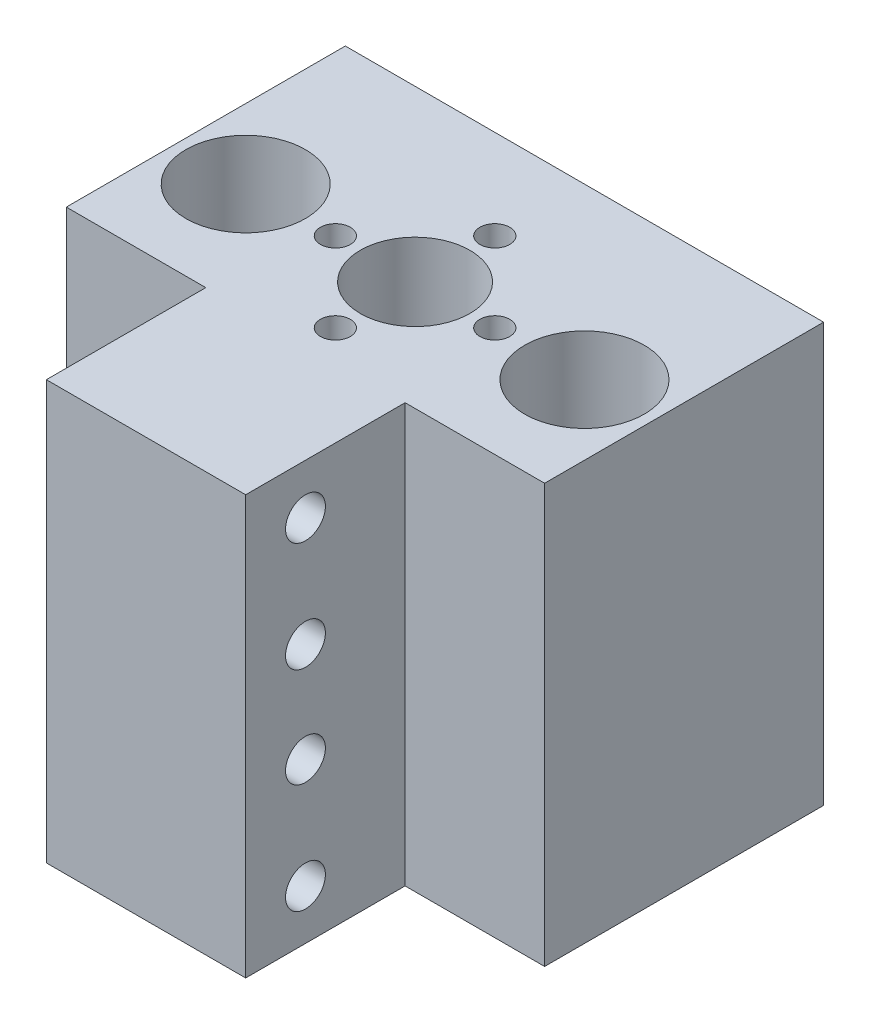
SolidWorks part; units mm, degrees
ref_plane "前基準面" through (0, 0, 0) normal (0, 0, 1) x (1, 0, 0)
ref_plane "上基準面" through (0, 0, 0) normal (0, 1, 0) x (1, 0, 0)
ref_plane "右基準面" through (0, 0, 0) normal (1, 0, 0) x (0, 0, -1)
sketch "草圖1" plane through (0, 0, 0) normal (0, 0, 1) x (1, 0, 0)
  line L1 (-24, 21) -> (24, 21)
  line L2 (-24, 21) -> (-24, -21)
  line L3 (-24, -21) -> (24, -21)
  line L4 (24, 21) -> (24, -21)
  point P4 (0, 21)
  point P6 (-24, 0)
  dimension "D1" = 48
  dimension "D2" = 42
extrude "填料-伸長1" add sketch "草圖1" along normal blind 38
sketch "草圖3" plane through (0, 21, 0) normal (0, 1, 0) x (1, 0, 0)
  line L0 (0, 0) -> (0, -38) construction
  line L1 (24, -38) -> (-24, -38) construction
  line L2 (24, 0) -> (-24, 0) construction
  circle A0 centre (17, -17) radius 6
  circle A1 centre (-17, -17) radius 6
  circle A2 centre (0, -17) radius 5.5
  circle A3 centre (0, -25) radius 1.5
  circle A4 centre (8, -17) radius 1.5
  circle A5 centre (0, -9) radius 1.5
  circle A6 centre (-8, -17) radius 1.5
  point P23 (0, -17)
  dimension "D1" = 12
  dimension "D4" = 11
  dimension "D5" = 3
  dimension "D2" = 17
  dimension "D3" = 17
  dimension "D6" = 8
  dimension "D7" = 17
  dimension "D8" = 4
extrude "除料-伸長2" cut sketch "草圖3" against normal through all
sketch "草圖9" plane through (0, 21, 0) normal (0, 1, 0) x (1, 0, 0)
  line L1 (-24, -38) -> (-10, -38)
  line L2 (-24, -38) -> (-24, -28)
  line L3 (-24, -28) -> (-10, -28)
  line L4 (-10, -38) -> (-10, -28)
  line L5 (24, -38) -> (10, -38)
  line L6 (24, -38) -> (24, -28)
  line L7 (24, -28) -> (10, -28)
  line L8 (10, -38) -> (10, -28)
  dimension "D1" = 10
  dimension "D2" = 14
  dimension "D3" = 14
  dimension "D4" = 10
extrude "除料-伸長6" cut sketch "草圖9" against normal through all
sketch "草圖10" plane through (0, 21, 0) normal (0, 1, 0) x (1, 0, 0)
  line L0 (-10, -28) -> (-24, -28) construction
  line L1 (-10, -38) -> (10, -38)
  line L2 (-10, -38) -> (-10, -44)
  line L3 (-10, -44) -> (10, -44)
  line L4 (10, -38) -> (10, -44)
  line L5 (10, -28) -> (10, -38) construction
  line L6 (-10, -38) -> (-10, -28) construction
  dimension "D1" = 16
  dimension "D2" = 20
extrude "填料-伸長3" add sketch "草圖10" against normal up to surface (42 mm away) up to face at (-8, -21, 18.5)
sketch "草圖11" plane through (10, 0, 0) normal (1, 0, 0) x (0, 0, -1)
  line L0 (-44, 0) -> (0, 0) construction
  line L1 (-44, -21) -> (-44, 21) construction
  line L2 (-28, -21) -> (-28, 21) construction
  line L3 (-28, -21) -> (-28, 21) construction
  line L4 (-28, 21) -> (-44, 21) construction
  circle A0 centre (-38, 16) radius 2
  circle A1 centre (-38, 5) radius 2
  circle A2 centre (-38, -5) radius 2
  circle A3 centre (-38, -16) radius 2
  dimension "D2" = 4
  dimension "D3" = 4
  dimension "D1" = 10
  dimension "D4" = 10
  dimension "D5" = 5
  dimension "D6" = 11
extrude "除料-伸長7" cut sketch "草圖11" against normal through all
